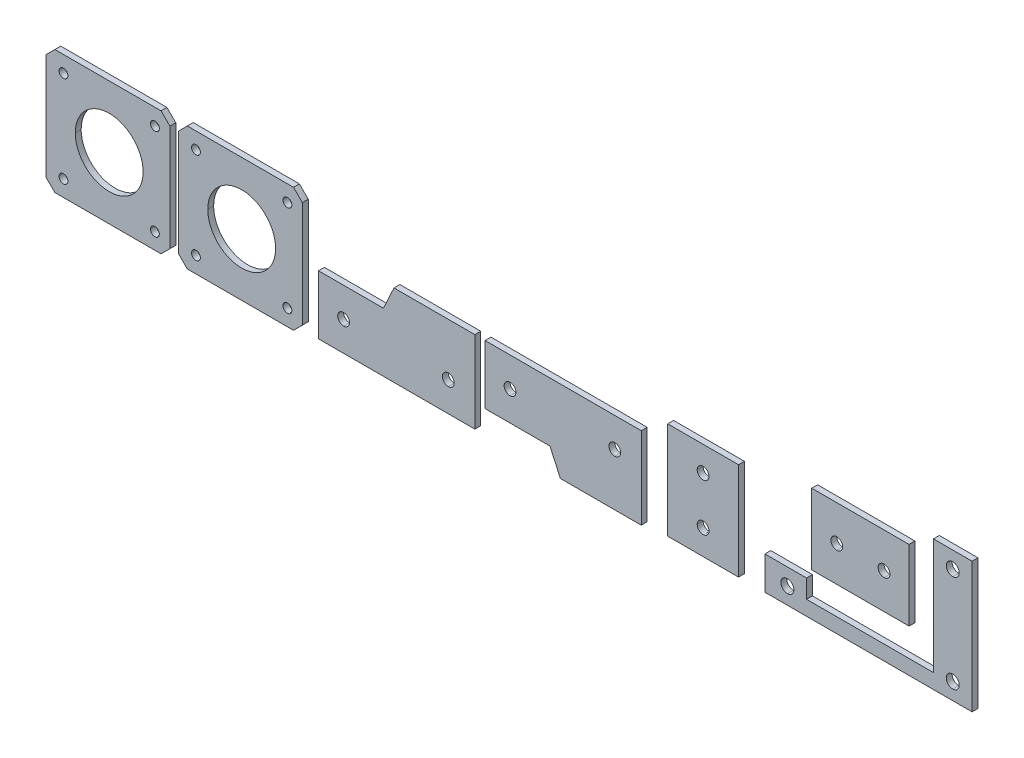
SolidWorks part; units mm, degrees
material "Corrugated Paper"
ref_plane "Front Plane" through (0, 0, 0) normal (0, 0, 1) x (1, 0, 0)
ref_plane "Top Plane" through (0, 0, 0) normal (0, 1, 0) x (1, 0, 0)
ref_plane "Right Plane" through (0, 0, 0) normal (1, 0, 0) x (0, 0, -1)
sketch "Model" plane through (0, 0, 0) normal (0, 0, 1) x (1, 0, 0)
  line L0 (245.6814, 14.4971) -> (245.6814, 3.2471)
  line L1 (245.6814, 3.2471) -> (315.9314, 3.2471)
  line L2 (315.9314, 3.2471) -> (315.9314, 47.4971)
  line L3 (315.9314, 47.4971) -> (302.8064, 47.4971)
  line L4 (302.8064, 47.4971) -> (302.8064, 8.2471)
  line L5 (302.8064, 8.2471) -> (259.8064, 8.2471)
  line L6 (259.8064, 8.2471) -> (259.8064, 14.4971)
  line L7 (259.8064, 14.4971) -> (245.6814, 14.4971)
  line L8 (294.5556, 41.7469) -> (294.5556, 17.7469)
  line L9 (294.5556, 17.7469) -> (261.5556, 17.7469)
  line L10 (261.5556, 17.7469) -> (261.5556, 41.7469)
  line L11 (261.5556, 41.7469) -> (294.5556, 41.7469)
  line L12 (236.7265, 3.2302) -> (212.7265, 3.2302)
  line L13 (212.7265, 3.2302) -> (212.7265, 36.2302)
  line L14 (212.7265, 36.2302) -> (236.7265, 36.2302)
  line L15 (236.7265, 36.2302) -> (236.7265, 3.2302)
  line L16 (119.9131, 29.7302) -> (116.3466, 21.9787)
  line L17 (116.3466, 21.9787) -> (94.3466, 21.9787)
  line L18 (94.3466, 21.9787) -> (94.3466, 1.9787)
  line L19 (94.3466, 1.9787) -> (147.3299, 1.9787)
  line L20 (147.3299, 1.9787) -> (147.3299, 29.7287)
  line L21 (147.3299, 29.7287) -> (119.9124, 29.7287)
  line L22 (176.3527, 1.9787) -> (172.7861, 9.7302)
  line L23 (172.7861, 9.7302) -> (150.7861, 9.7302)
  line L24 (150.7861, 9.7302) -> (150.7861, 29.7302)
  line L25 (150.7861, 29.7302) -> (203.7694, 29.7302)
  line L26 (203.7694, 29.7302) -> (203.7694, 1.9802)
  line L27 (203.7694, 1.9802) -> (176.352, 1.9802)
  line L28 (49.8518, 0.2516) -> (85.8518, 0.2516)
  line L29 (85.8518, 0.2516) -> (88.8518, 3.2516)
  line L30 (88.8518, 3.2516) -> (88.8518, 39.2516)
  line L31 (88.8518, 39.2516) -> (85.8518, 42.2516)
  line L32 (85.8518, 42.2516) -> (49.8518, 42.2516)
  line L33 (49.8518, 42.2516) -> (46.8518, 39.2516)
  line L34 (46.8518, 39.2516) -> (46.8518, 3.2516)
  line L35 (46.8518, 3.2516) -> (49.8518, 0.2516)
  line L36 (4.9314, 0.2427) -> (40.9314, 0.2427)
  line L37 (40.9314, 0.2427) -> (43.9314, 3.2428)
  line L38 (43.9314, 3.2428) -> (43.9314, 39.2427)
  line L39 (43.9314, 39.2427) -> (40.9314, 42.2427)
  line L40 (40.9314, 42.2427) -> (4.9314, 42.2427)
  line L41 (4.9314, 42.2427) -> (1.9314, 39.2427)
  line L42 (1.9314, 39.2427) -> (1.9314, 3.2428)
  line L43 (1.9314, 3.2428) -> (4.9314, 0.2427)
  spline S0 degree 3 poles (253.3064, 6.6721) (252.0914, 6.6721) (251.1064, 7.6571) (251.1064, 8.8721) (251.1064, 10.0871) (252.0914, 11.0721) (253.3064, 11.0721) knots 2 2 2 2 3 3 3 4 4 4 4
  spline S1 degree 3 poles (253.3064, 11.0721) (254.5214, 11.0721) (255.5064, 10.0871) (255.5064, 8.8721) (255.5064, 7.6571) (254.5214, 6.6721) (253.3064, 6.6721) knots 0 0 0 0 1 1 1 2 2 2 2
  spline S2 degree 3 poles (309.3689, 39.6721) (308.1538, 39.6721) (307.1689, 40.6571) (307.1689, 41.8721) (307.1689, 43.0871) (308.1538, 44.0721) (309.3689, 44.0721) knots 2 2 2 2 3 3 3 4 4 4 4
  spline S3 degree 3 poles (309.3689, 44.0721) (310.5839, 44.0721) (311.5689, 43.0871) (311.5689, 41.8721) (311.5689, 40.6571) (310.5839, 39.6721) (309.3689, 39.6721) knots 0 0 0 0 1 1 1 2 2 2 2
  spline S4 degree 3 poles (309.3689, 6.6721) (308.1538, 6.6721) (307.1689, 7.6571) (307.1689, 8.8721) (307.1689, 10.0871) (308.1538, 11.0721) (309.3689, 11.0721) knots 2 2 2 2 3 3 3 4 4 4 4
  spline S5 degree 3 poles (309.3689, 11.0721) (310.5839, 11.0721) (311.5689, 10.0871) (311.5689, 8.8721) (311.5689, 7.6571) (310.5839, 6.6721) (309.3689, 6.6721) knots 0 0 0 0 1 1 1 2 2 2 2
  spline S6 degree 3 poles (270.0388, 27.7469) (271.1434, 27.7469) (272.0388, 28.6424) (272.0388, 29.7469) (272.0388, 30.8515) (271.1434, 31.7469) (270.0388, 31.7469) knots 2 2 2 2 3 3 3 4 4 4 4
  spline S7 degree 3 poles (270.0388, 31.7469) (268.9343, 31.7469) (268.0388, 30.8515) (268.0388, 29.7469) (268.0388, 28.6424) (268.9343, 27.7469) (270.0388, 27.7469) knots 0 0 0 0 1 1 1 2 2 2 2
  spline S8 degree 3 poles (286.0723, 27.7469) (287.1769, 27.7469) (288.0723, 28.6423) (288.0723, 29.7469) (288.0723, 30.8515) (287.1769, 31.7469) (286.0723, 31.7469) knots 2 2 2 2 3 3 3 4 4 4 4
  spline S9 degree 3 poles (286.0723, 31.7469) (284.9677, 31.7469) (284.0723, 30.8515) (284.0723, 29.7469) (284.0723, 28.6423) (284.9677, 27.7469) (286.0723, 27.7469) knots 0 0 0 0 1 1 1 2 2 2 2
  spline S10 degree 3 poles (222.7265, 27.7469) (222.7265, 26.6424) (223.6219, 25.7469) (224.7265, 25.7469) (225.8311, 25.7469) (226.7265, 26.6424) (226.7265, 27.7469) knots 2 2 2 2 3 3 3 4 4 4 4
  spline S11 degree 3 poles (226.7265, 27.7469) (226.7265, 28.8515) (225.8311, 29.7469) (224.7265, 29.7469) (223.6219, 29.7469) (222.7265, 28.8515) (222.7265, 27.7469) knots 0 0 0 0 1 1 1 2 2 2 2
  spline S12 degree 3 poles (222.7265, 11.7135) (222.7265, 10.6089) (223.6219, 9.7135) (224.7265, 9.7135) (225.831, 9.7135) (226.7265, 10.6089) (226.7265, 11.7135) knots 2 2 2 2 3 3 3 4 4 4 4
  spline S13 degree 3 poles (226.7265, 11.7135) (226.7265, 12.8181) (225.831, 13.7135) (224.7265, 13.7135) (223.6219, 13.7135) (222.7265, 12.8181) (222.7265, 11.7135) knots 0 0 0 0 1 1 1 2 2 2 2
  spline S14 degree 3 poles (102.8299, 9.9787) (103.9344, 9.9787) (104.8299, 10.8741) (104.8299, 11.9787) (104.8299, 13.0833) (103.9344, 13.9787) (102.8299, 13.9787) knots 2 2 2 2 3 3 3 4 4 4 4
  spline S15 degree 3 poles (102.8299, 13.9787) (101.7253, 13.9787) (100.8299, 13.0833) (100.8299, 11.9787) (100.8299, 10.8741) (101.7253, 9.9787) (102.8299, 9.9787) knots 0 0 0 0 1 1 1 2 2 2 2
  spline S16 degree 3 poles (138.3299, 9.9787) (139.4344, 9.9787) (140.3299, 10.8741) (140.3299, 11.9787) (140.3299, 13.0833) (139.4344, 13.9787) (138.3299, 13.9787) knots 2 2 2 2 3 3 3 4 4 4 4
  spline S17 degree 3 poles (138.3299, 13.9787) (137.2253, 13.9787) (136.3299, 13.0833) (136.3299, 11.9787) (136.3299, 10.8741) (137.2253, 9.9787) (138.3299, 9.9787) knots 0 0 0 0 1 1 1 2 2 2 2
  spline S18 degree 3 poles (159.2694, 21.7302) (160.374, 21.7302) (161.2694, 20.8348) (161.2694, 19.7302) (161.2694, 18.6256) (160.374, 17.7302) (159.2694, 17.7302) knots 2 2 2 2 3 3 3 4 4 4 4
  spline S19 degree 3 poles (159.2694, 17.7302) (158.1649, 17.7302) (157.2694, 18.6256) (157.2694, 19.7302) (157.2694, 20.8348) (158.1649, 21.7302) (159.2694, 21.7302) knots 0 0 0 0 1 1 1 2 2 2 2
  spline S20 degree 3 poles (194.7694, 21.7302) (195.874, 21.7302) (196.7694, 20.8348) (196.7694, 19.7302) (196.7694, 18.6256) (195.874, 17.7302) (194.7694, 17.7302) knots 2 2 2 2 3 3 3 4 4 4 4
  spline S21 degree 3 poles (194.7694, 17.7302) (193.6649, 17.7302) (192.7694, 18.6256) (192.7694, 19.7302) (192.7694, 20.8348) (193.6649, 21.7302) (194.7694, 21.7302) knots 0 0 0 0 1 1 1 2 2 2 2
  spline S22 degree 3 poles (51.2777, 36.7427) (51.2777, 37.5712) (51.9493, 38.2427) (52.7777, 38.2427) (53.6061, 38.2427) (54.2777, 37.5712) (54.2777, 36.7427) knots 2 2 2 2 3 3 3 4 4 4 4
  spline S23 degree 3 poles (54.2777, 36.7427) (54.2777, 35.9143) (53.6061, 35.2427) (52.7777, 35.2427) (51.9493, 35.2427) (51.2777, 35.9143) (51.2777, 36.7427) knots 0 0 0 0 1 1 1 2 2 2 2
  spline S24 degree 3 poles (51.2777, 5.7427) (51.2777, 6.5712) (51.9493, 7.2428) (52.7777, 7.2428) (53.6061, 7.2428) (54.2777, 6.5712) (54.2777, 5.7427) knots 2 2 2 2 3 3 3 4 4 4 4
  spline S25 degree 3 poles (54.2777, 5.7427) (54.2777, 4.9143) (53.6061, 4.2427) (52.7777, 4.2427) (51.9493, 4.2427) (51.2777, 4.9143) (51.2777, 5.7427) knots 0 0 0 0 1 1 1 2 2 2 2
  spline S26 degree 3 poles (82.2777, 5.7427) (82.2777, 6.5712) (82.9493, 7.2428) (83.7777, 7.2428) (84.6061, 7.2428) (85.2777, 6.5712) (85.2777, 5.7427) knots 2 2 2 2 3 3 3 4 4 4 4
  spline S27 degree 3 poles (85.2777, 5.7427) (85.2777, 4.9143) (84.6061, 4.2427) (83.7777, 4.2427) (82.9493, 4.2427) (82.2777, 4.9143) (82.2777, 5.7427) knots 0 0 0 0 1 1 1 2 2 2 2
  spline S28 degree 3 poles (82.2777, 36.7427) (82.2777, 37.5712) (82.9493, 38.2427) (83.7777, 38.2427) (84.6061, 38.2427) (85.2777, 37.5712) (85.2777, 36.7427) knots 2 2 2 2 3 3 3 4 4 4 4
  spline S29 degree 3 poles (85.2777, 36.7427) (85.2777, 35.9143) (84.6061, 35.2427) (83.7777, 35.2427) (82.9493, 35.2427) (82.2777, 35.9143) (82.2777, 36.7427) knots 0 0 0 0 1 1 1 2 2 2 2
  spline S30 degree 3 poles (56.7777, 21.2427) (56.7777, 27.594) (61.9264, 32.7427) (68.2777, 32.7427) (74.629, 32.7427) (79.7777, 27.594) (79.7777, 21.2427) knots 2 2 2 2 3 3 3 4 4 4 4
  spline S31 degree 3 poles (79.7777, 21.2427) (79.7777, 14.8915) (74.629, 9.7427) (68.2777, 9.7427) (61.9264, 9.7427) (56.7777, 14.8915) (56.7777, 21.2427) knots 0 0 0 0 1 1 1 2 2 2 2
  spline S32 degree 3 poles (6.3573, 36.7339) (6.3573, 37.5623) (7.0289, 38.2339) (7.8573, 38.2339) (8.6857, 38.2339) (9.3573, 37.5623) (9.3573, 36.7339) knots 2 2 2 2 3 3 3 4 4 4 4
  spline S33 degree 3 poles (9.3573, 36.7339) (9.3573, 35.9055) (8.6857, 35.2339) (7.8573, 35.2339) (7.0289, 35.2339) (6.3573, 35.9055) (6.3573, 36.7339) knots 0 0 0 0 1 1 1 2 2 2 2
  spline S34 degree 3 poles (6.3573, 5.7339) (6.3573, 6.5623) (7.0289, 7.2339) (7.8573, 7.2339) (8.6857, 7.2339) (9.3573, 6.5623) (9.3573, 5.7339) knots 2 2 2 2 3 3 3 4 4 4 4
  spline S35 degree 3 poles (9.3573, 5.7339) (9.3573, 4.9055) (8.6857, 4.2339) (7.8573, 4.2339) (7.0289, 4.2339) (6.3573, 4.9055) (6.3573, 5.7339) knots 0 0 0 0 1 1 1 2 2 2 2
  spline S36 degree 3 poles (37.3573, 5.7339) (37.3573, 6.5623) (38.0289, 7.2339) (38.8573, 7.2339) (39.6857, 7.2339) (40.3573, 6.5623) (40.3573, 5.7339) knots 2 2 2 2 3 3 3 4 4 4 4
  spline S37 degree 3 poles (40.3573, 5.7339) (40.3573, 4.9055) (39.6857, 4.2339) (38.8573, 4.2339) (38.0289, 4.2339) (37.3573, 4.9055) (37.3573, 5.7339) knots 0 0 0 0 1 1 1 2 2 2 2
  spline S38 degree 3 poles (37.3573, 36.7339) (37.3573, 37.5623) (38.0289, 38.2339) (38.8574, 38.2339) (39.6857, 38.2339) (40.3573, 37.5623) (40.3573, 36.7339) knots 2 2 2 2 3 3 3 4 4 4 4
  spline S39 degree 3 poles (40.3573, 36.7339) (40.3573, 35.9055) (39.6857, 35.2339) (38.8574, 35.2339) (38.0289, 35.2339) (37.3573, 35.9055) (37.3573, 36.7339) knots 0 0 0 0 1 1 1 2 2 2 2
  spline S40 degree 3 poles (11.8573, 21.2339) (11.8573, 27.5852) (17.006, 32.7339) (23.3573, 32.7339) (29.7086, 32.7339) (34.8573, 27.5852) (34.8573, 21.2339) knots 2 2 2 2 3 3 3 4 4 4 4
  spline S41 degree 3 poles (34.8573, 21.2339) (34.8573, 14.8826) (29.7086, 9.7339) (23.3573, 9.7339) (17.006, 9.7339) (11.8573, 14.8826) (11.8573, 21.2339) knots 0 0 0 0 1 1 1 2 2 2 2
extrude "Boss-Extrude1" add sketch "Model" along normal blind 2 contours L42 L43 L36 L37 L38 L39 L40 L41 S32 S33 S34 S35 S36 S37 S38 S39 S40 S41 | L34 L35 L28 L29 L30 L31 L32 L33 S22 S23 S24 S25 S26 S27 S28 S29 S30 S31 | L20 L21 L16 L17 L18 L19 S17 S16 S15 S14 | L27 L26 L25 L24 L23 L22 S18 S19 S20 S21 | L15 L14 L13 L12 S13 S12 S11 S10 | L11 L10 L9 L8 S9 S8 S7 S6 | L6 L7 L0 L1 L2 L3 L4 L5 S0 S1 S2 S3 S4 S5
